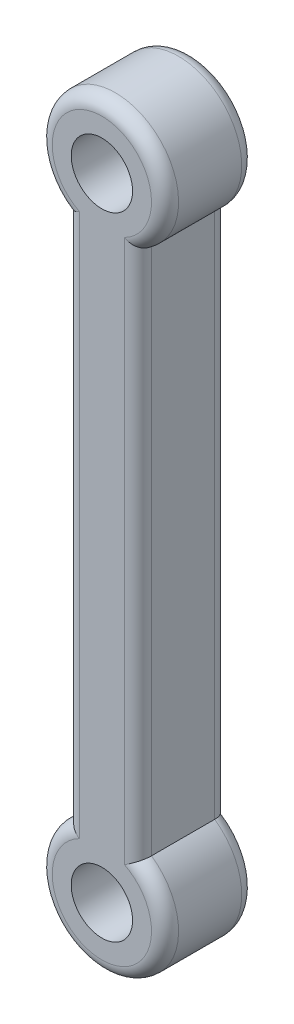
SolidWorks part; units mm, degrees
ref_plane "Alzado" through (0, 0, 0) normal (0, 0, 1) x (1, 0, 0)
ref_plane "Planta" through (0, 0, 0) normal (0, 1, 0) x (1, 0, 0)
ref_plane "Vista lateral" through (0, 0, 0) normal (1, 0, 0) x (0, 0, -1)
sketch "Croquis1" plane through (0, 0, 0) normal (0, 0, 1) x (1, 0, 0)
  line L0 (0, 17.5) -> (0, -17.5) construction
  line L2 (2, -14.6277) -> (2, 14.6277)
  line L4 (-2, -14.6277) -> (-2, 14.6277)
  line L5 (2, -14.6277) -> (-2, 14.6277) construction
  line L6 (2, 14.6277) -> (-2, -14.6277) construction
  arc A0 (-2, -14.6277) -> (2, -14.6277) centre (0, -17.5) ccw
  circle A1 centre (0, -17.5) radius 1.7
  arc A2 (2, 14.6277) -> (-2, 14.6277) centre (0, 17.5) ccw
  circle A3 centre (0, 17.5) radius 1.7
  point P0 (0, 0)
  dimension "D2" = 3.4
  dimension "D3" = 7
  dimension "D1" = 35
  dimension "D4" = 4
extrude "Saliente-Extruir1" add sketch "Croquis1" along normal blind 5
fillet "Redondeo1" radius 0.75 8 edges at (0, 21, 0) (-2, 0, 0) (2, 0, 0) (0, -21, 0) (0, -21, 5) (0, 21, 5) (-2, 0, 5) (2, 0, 5)
